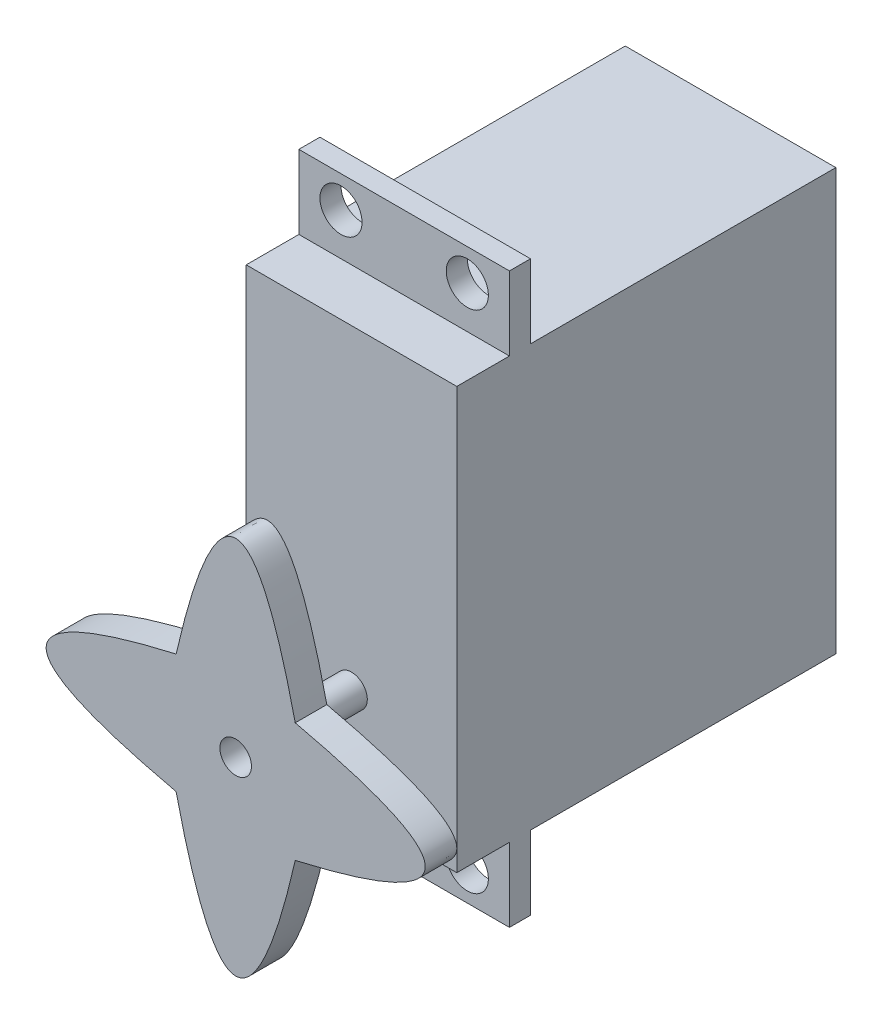
SolidWorks part; units mm, degrees
ref_plane "前视基准面" through (0, 0, 0) normal (0, 0, 1) x (1, 0, 0)
ref_plane "上视基准面" through (0, 0, 0) normal (0, 1, 0) x (1, 0, 0)
ref_plane "右视基准面" through (0, 0, 0) normal (1, 0, 0) x (0, 0, -1)
sketch "草图1" plane through (0, 0, 0) normal (0, 0, 1) x (1, 0, 0)
  line L1 (0, 0) -> (20, 0)
  line L2 (0, 0) -> (0, 40)
  line L3 (0, 40) -> (20, 40)
  line L4 (20, 0) -> (20, 40)
extrude "凸台-拉伸1" add sketch "草图1" along normal blind 36
sketch "草图2" plane through (0, 0, 0) normal (0, -1, 0) x (1, 0, 0)
  line L0 (0, 36) -> (0, 0) construction
  line L1 (0, 29) -> (20, 29)
  line L2 (0, 29) -> (0, 31)
  line L3 (0, 31) -> (20, 31)
  line L4 (20, 29) -> (20, 31)
  line L5 (20, 36) -> (20, 0) construction
  point P8 (0, 0)
  point P9 (0, 0)
extrude "凸台-拉伸2" add sketch "草图2" along normal blind 7 and the other way blind 47
sketch "草图3" plane through (0, 0, 31) normal (0, 0, 1) x (1, 0, 0)
  circle A0 centre (4, -4) radius 2
  circle A1 centre (16, -4) radius 2
  circle A2 centre (4, 44) radius 2
  circle A3 centre (16, 44) radius 2
  point P6 (0, 0)
extrude "切除-拉伸1" cut sketch "草图3" against normal up to next
sketch "草图4" plane through (0, 0, 36) normal (0, 0, 1) x (1, 0, 0)
  circle A0 centre (10, 10) radius 1.5
extrude "凸台-拉伸3" add sketch "草图4" along normal blind 8
sketch "草图5" plane through (0, 0, 44) normal (0, 0, 1) x (1, 0, 0)
  line L0 (10, 10) -> (-8, 10)
  line L1 (10, 10) -> (-2.7279, 22.7279)
  line L2 (10, 10) -> (10, 28)
  line L3 (10, 10) -> (22.7279, 22.7279)
  line L4 (10, 10) -> (28, 10)
  line L5 (10, 10) -> (22.7279, -2.7279)
  line L6 (10, 10) -> (10, -8)
  line L7 (10, 10) -> (-2.7279, -2.7279)
  circle A0 centre (10, 10) radius 18
  circle A1 centre (10, 10) radius 8
  spline S0 degree 2 poles (4.3431, 4.3431) (-20.3431, 10) (4.3431, 15.6569) knots 0 0 0 1 1 1
  spline S1 degree 2 poles (4.3431, 15.6569) (10, 40.3431) (15.6569, 15.6569) knots 0 0 0 1 1 1
  spline S2 degree 2 poles (4.3431, 4.3431) (10, -20.3431) (15.6569, 4.3431) knots 0 0 0 1 1 1
  spline S3 degree 2 poles (15.6569, 4.3431) (40.3431, 10) (15.6569, 15.6569) knots 0 0 0 1 1 1
  point P14 (10, 10)
  circle M2 centre (10, 10) radius 1.5
  dimension "D1" = 8
extrude "凸台-拉伸4" add sketch "草图5" along normal blind 3 separate body contours A1 S2 L6 | L6 S2 A1 | L5 A1 L4 M2 | A1 S3 L4 | L4 S3 A1 | L4 A1 L3 M2 | L3 A1 L2 M2 | S1 L2 A1 | S1 A1 L2 | L2 A1 L1 M2 | L1 A1 L0 M2 | S0 L0 A1 | S0 A1 L0 | L0 A1 L7 M2 | L7 A1 L6 M2 | L6 A1 L5 M2
